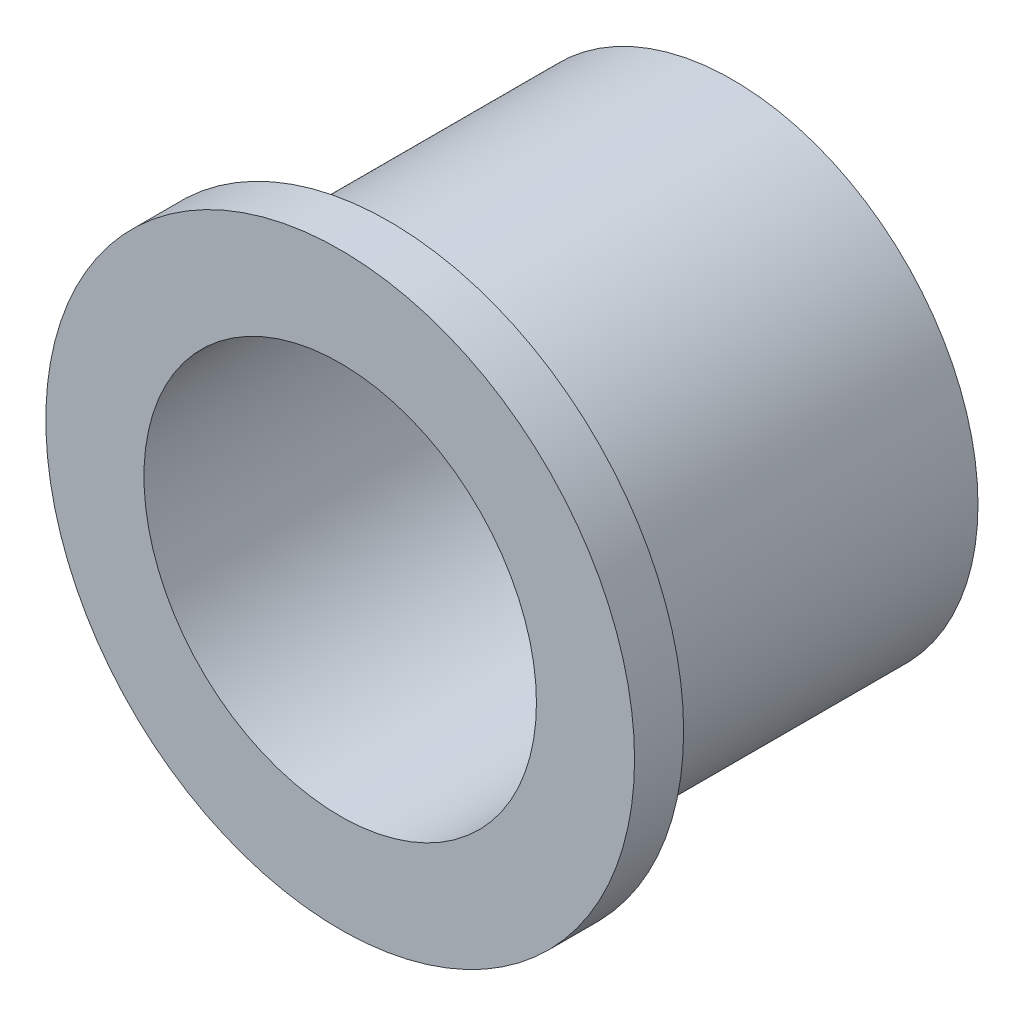
SolidWorks part; units mm, degrees
material "Brąz cynowy łożyskowy"
ref_plane "Płaszczyzna przednia" through (0, 0, 0) normal (0, 0, 1) x (1, 0, 0)
ref_plane "Płaszczyzna górna" through (0, 0, 0) normal (0, 1, 0) x (1, 0, 0)
ref_plane "Płaszczyzna prawa" through (0, 0, 0) normal (1, 0, 0) x (0, 0, -1)
sketch "Szkic1" plane through (0, 0, 0) normal (1, 0, 0) x (0, 0, -1)
  line L0 (0, 0) -> (14982.0419, 0) construction
  line L1 (0, 9) -> (0, 6)
  line L2 (0, 6) -> (12, 6)
  line L3 (12, 6) -> (12, 7.5)
  line L4 (12, 7.5) -> (1.5, 7.5)
  line L5 (1.5, 7.5) -> (1.5, 9)
  line L6 (1.5, 9) -> (0, 9)
  dimension "D1" = 12
  dimension "D2" = 18
  dimension "D3" = 12
  dimension "D4" = 15
  dimension "D5" = 1.5
revolve "Obrót1" add sketch "Szkic1" angle 360 about L0
